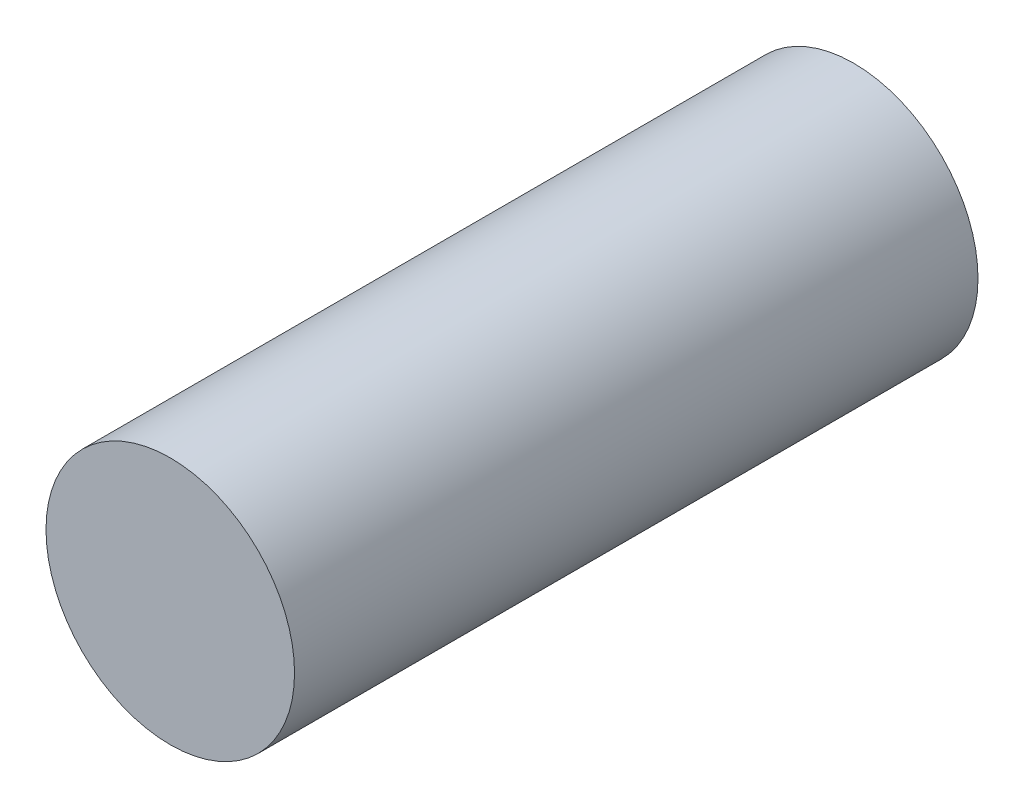
SolidWorks part; units mm, degrees
material "Stainless Steel (ferritic)"
ref_plane "Ebene vorne" through (0, 0, 0) normal (0, 0, 1) x (1, 0, 0)
ref_plane "Ebene oben" through (0, 0, 0) normal (0, 1, 0) x (1, 0, 0)
ref_plane "Ebene rechts" through (0, 0, 0) normal (1, 0, 0) x (0, 0, -1)
sketch "Sketch1" plane through (0, 0, 0) normal (0, 0, 1) x (1, 0, 0)
  circle A0 centre (0, 0) radius 2
  dimension "D1" = 4
extrude "Boss-Extrude1" add sketch "Sketch1" along normal blind 11
